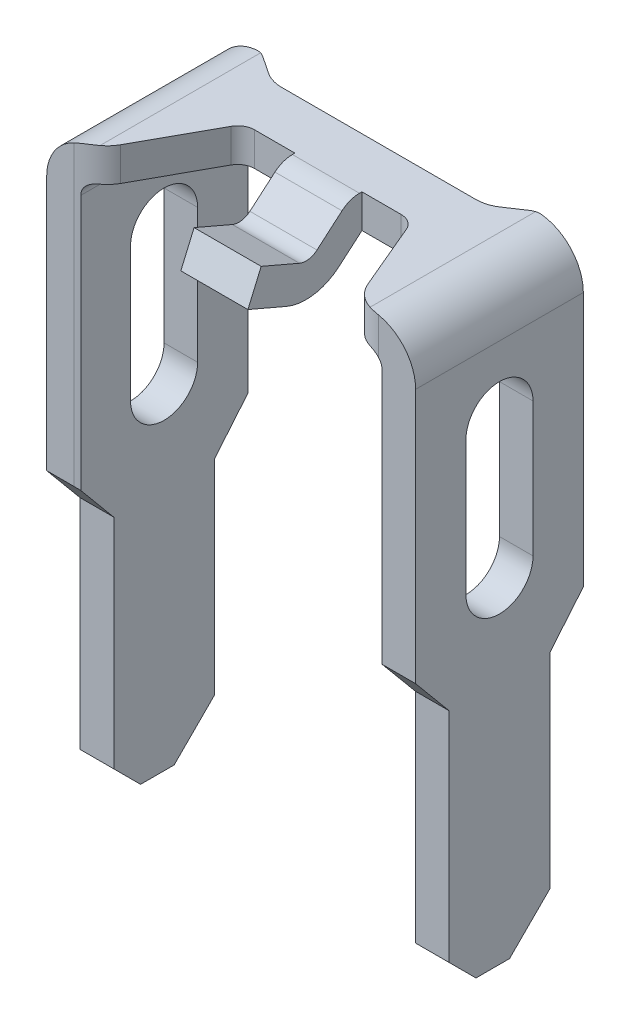
SolidWorks part; units mm, degrees
ref_plane "Front Plane" through (0, 0, 0) normal (0, 0, 1) x (1, 0, 0)
ref_plane "Top Plane" through (0, 0, 0) normal (0, 1, 0) x (1, 0, 0)
ref_plane "Right Plane" through (0, 0, 0) normal (1, 0, 0) x (0, 0, -1)
sketch "Sketch1" plane through (0, 0, 0) normal (0, 0, 1) x (1, 0, 0)
  line L0 (-2.75, -4) -> (-2.75, 4.05)
  line L1 (-2.25, -4.25) -> (-2.25, 4.25) construction
  line L2 (-2.25, -4) -> (-2.25, 4.05)
  line L3 (-2.05, 4.25) -> (2.05, 4.25)
  line L4 (2.25, -4) -> (2.25, 4.05)
  line L5 (2.2086, 4.1718) -> (2.25, 4.25) construction
  line L6 (-2.25, 4.25) -> (-2.2086, 4.1718) construction
  line L7 (-2.05, 4.75) -> (2.05, 4.75)
  line L8 (2.75, -4) -> (2.75, 4.05)
  line L9 (2.75, -4.75) -> (2.75, 4.75) construction
  line L12 (-2.75, -4.75) -> (-2.75, 4.75) construction
  line L13 (-2.25, 4.25) -> (2.25, 4.25) construction
  line L14 (-2.75, -4.75) -> (2.75, -4.75) construction
  line L15 (-2.25, -4.25) -> (2.25, -4.25) construction
  line L16 (2.25, -4.25) -> (2.25, 4.25) construction
  line L17 (-2.75, 4.75) -> (2.75, 4.75) construction
  line L18 (-2.75, -4) -> (-2.25, -4)
  line L19 (2.25, -4) -> (2.75, -4)
  arc A0 (-2.25, 4.05) -> (-2.05, 4.25) centre (-2.05, 4.05) cw
  arc A1 (2.05, 4.25) -> (2.25, 4.05) centre (2.05, 4.05) cw
  arc A2 (2.05, 4.75) -> (2.75, 4.05) centre (2.05, 4.05) cw
  arc A3 (-2.75, 4.05) -> (-2.05, 4.75) centre (-2.05, 4.05) cw
  point P0 (0, 0)
  dimension "D4" = 0.2
  dimension "D5" = 0.7
  dimension "D1" = 4.5
  dimension "D2" = 4.25
  dimension "D6" = 4
  dimension "D3" = 0.5
extrude "Boss-Extrude1" add sketch "Sketch1" along normal blind 2.5
sketch "Sketch2" plane through (0, 4.75, 0) normal (0, 1, 0) x (1, 0, 0)
  line L0 (2.05, 0) -> (-2.05, 0) construction
  line L1 (-2.05, 0) -> (-1.726, -0.216)
  line L2 (-1.4486, -0.3) -> (1.4486, -0.3)
  line L3 (1.726, -0.216) -> (2.05, 0)
  line L4 (2.05, 0) -> (2.05, 0.5475)
  line L5 (2.05, 0.5475) -> (-2.05, 0.5475)
  line L6 (-2.05, 0.5475) -> (-2.05, 0)
  line L7 (2.05, -2.5) -> (-2.05, -2.5) construction
  line L13 (-2.75, -2.5) -> (-2.3452, -2.5)
  line L15 (-1.9074, -2.2415) -> (-1.3213, -1.1792)
  line L16 (-1.1024, -1.05) -> (1.0843, -1.05)
  line L17 (1.3145, -1.2026) -> (1.7341, -2.1948)
  line L19 (2.1946, -2.5) -> (2.75, -2.5)
  line L20 (2.75, -2.5) -> (2.75, -3.0561)
  line L21 (2.75, -3.0561) -> (-2.75, -3.0561)
  line L22 (-2.75, -3.0561) -> (-2.75, -2.5)
  arc A0 (1.7341, -2.1948) -> (2.1946, -2.5) centre (2.1946, -2) ccw
  arc A1 (-2.3452, -2.5) -> (-1.9074, -2.2415) centre (-2.3452, -2) ccw
  arc A2 (1.0843, -1.05) -> (1.3145, -1.2026) centre (1.0843, -1.3) cw
  arc A3 (-1.3213, -1.1792) -> (-1.1024, -1.05) centre (-1.1024, -1.3) cw
  arc A4 (1.4486, -0.3) -> (1.726, -0.216) centre (1.4486, 0.2) ccw
  arc A5 (-1.726, -0.216) -> (-1.4486, -0.3) centre (-1.4486, 0.2) ccw
  point P15 (1.6, -0.3)
  point P22 (-2.05, -2.5)
  point P31 (1.25, -1.05)
  point P34 (-1.25, -1.05)
  point P36 (-1.6, -0.3)
  dimension "D8" = 0.5
  dimension "D9" = 0.25
  dimension "D6" = 0.5
  dimension "D1" = 0.3
  dimension "D2" = 0.45
  dimension "D3" = 2.5
  dimension "D4" = 1.25
  dimension "D5" = 0.45
  dimension "D7" = 1.45
extrude "Cut-Extrude1" cut sketch "Sketch2" against normal blind 10.5
fillet "Fillet1" radius 0.25 2 edges at (2.05, 4.5, 0) (-2.05, 4.5, 0)
sketch "Sketch3" plane through (0, 0, 0) normal (1, 0, 0) x (0, 0, -1)
  line L0 (-1.25, -4.25) -> (-1.25, 4.05) construction
  line L1 (0, 4.05) -> (0, -4) construction
  line L2 (-2.5, 4.05) -> (0, 4.05) construction
  line L3 (0, 0.25) -> (-0.5, -0.35)
  line L5 (-0.5, -0.35) -> (-0.5, -4.3963)
  line L6 (-0.5, -4.3963) -> (0.8764, -4.3963)
  line L7 (0.8764, -4.3963) -> (0.8764, 0.25)
  line L8 (0.8764, 0.25) -> (0, 0.25)
  line L9 (-2.5, 0.25) -> (-2, -0.35)
  line L10 (-2.5, 4.05) -> (-2.5, -4) construction
  line L11 (-2, -0.35) -> (-2, -4.8963)
  line L12 (-2, -4.8963) -> (-3.0703, -4.8963)
  line L13 (-3.0703, -4.8963) -> (-3.0703, 0.25)
  line L14 (-3.0703, 0.25) -> (-2.5, 0.25)
  line L15 (-2.4036, 4.75) -> (-0.0117, 4.75) construction
  line L16 (-1.25, 3.0246) -> (-1.25, 1.0246) construction
  line L17 (-0.75, 3.0246) -> (-0.75, 1.0246)
  line L18 (-1.75, 3.0246) -> (-1.75, 1.0246)
  arc A0 (-0.75, 3.0246) -> (-1.75, 3.0246) centre (-1.25, 3.0246) ccw
  arc A1 (-1.75, 1.0246) -> (-0.75, 1.0246) centre (-1.25, 1.0246) ccw
  point P22 (-1.25, 2.0246)
  dimension "D8" = 0.5
  dimension "D1" = 4.5
  dimension "D2" = 4.5
  dimension "D3" = 0.75
  dimension "D4" = 0.75
  dimension "D5" = 0.6
  dimension "D6" = 0.6
  dimension "D7" = 2
extrude "Cut-Extrude2" cut sketch "Sketch3" against normal mid plane 10.5
sketch "Sketch4" plane through (0, 0, 0) normal (1, 0, 0) x (0, 0, -1)
  line L0 (-1.05, 4.25) -> (-1.3952, 3.9541)
  line L1 (-2.1794, 3.8345) -> (-2.75, 4.0797)
  line L2 (-2.75, 4.0797) -> (-2.5526, 4.5391)
  line L3 (-2.5526, 4.5391) -> (-1.982, 4.2939)
  line L4 (-1.7206, 4.3338) -> (-1.3473, 4.6537)
  line L5 (-1.05, 4.75) -> (-1.087, 4.75)
  line L6 (-1.05, 4.75) -> (-1.05, 4.25)
  arc A0 (-1.3473, 4.6537) -> (-1.087, 4.75) centre (-1.087, 4.35) cw
  arc A1 (-1.982, 4.2939) -> (-1.7206, 4.3338) centre (-1.8833, 4.5236) ccw
  arc A2 (-1.3952, 3.9541) -> (-2.1794, 3.8345) centre (-1.8833, 4.5236) cw
  point P15 (-1.75, 3.65)
  dimension "D6" = 0.4
  dimension "D7" = 0.25
  dimension "D8" = 0.75
  dimension "D1" = 0.7
  dimension "D2" = 0.6
  dimension "D3" = 1
  dimension "D4" = 0.5
  dimension "D5" = 0.5
extrude "Boss-Extrude2" add sketch "Sketch4" along normal mid plane 1
chamfer "Chamfer1" distance 0.6 angle 45 2 edges at (2.5, -4, 0.5) (-2.5, -4, 0.5)
chamfer "Chamfer2" distance 0.4 angle 45 2 edges at (-2.5, -4, 2) (2.5, -4, 2)
